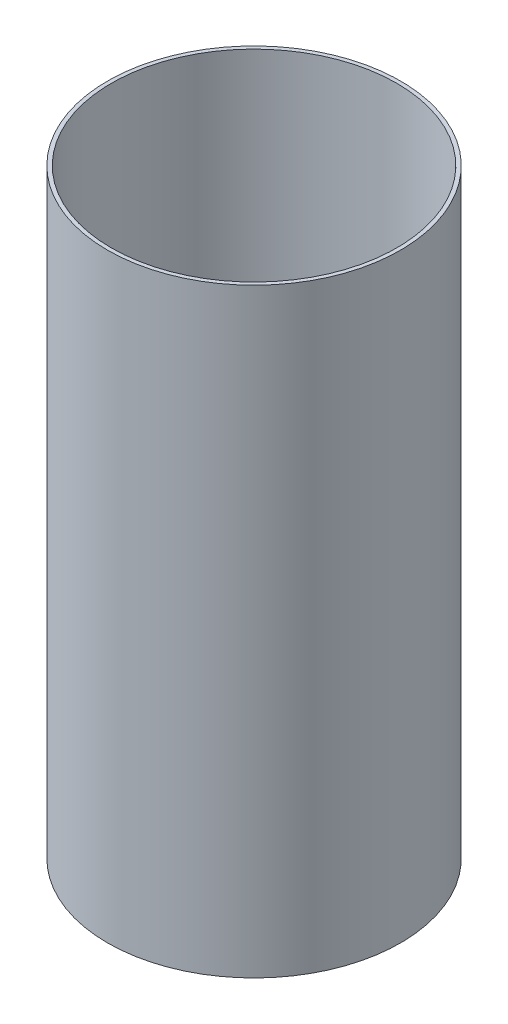
SolidWorks part; units mm, degrees
material "E-Glass Fiber"
ref_plane "Front Plane" through (0, 0, 0) normal (0, 0, 1) x (1, 0, 0)
ref_plane "Top Plane" through (0, 0, 0) normal (0, 1, 0) x (1, 0, 0)
ref_plane "Right Plane" through (0, 0, 0) normal (1, 0, 0) x (0, 0, -1)
sketch "Sketch1" plane through (0, 0, 0) normal (0, 1, 0) x (1, 0, 0)
  circle A0 centre (0, 0) radius 74.2
  circle A1 centre (0, 0) radius 76.2
  dimension "D1" = 148.4
  dimension "D2" = 152.4
extrude "Boss-Extrude1" add sketch "Sketch1" along normal blind 312
